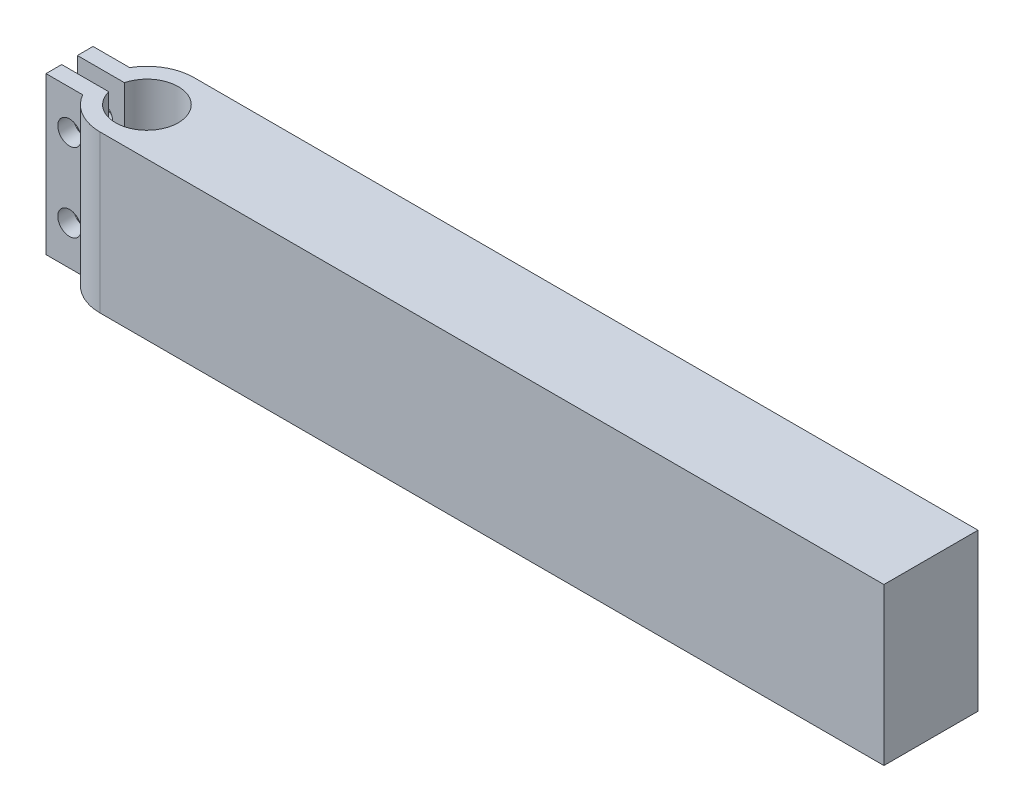
SolidWorks part; units mm, degrees
ref_plane "Plano frontal" through (0, 0, 0) normal (0, 0, 1) x (1, 0, 0)
ref_plane "Plano superior" through (0, 0, 0) normal (0, 1, 0) x (1, 0, 0)
ref_plane "Plano direito" through (0, 0, 0) normal (1, 0, 0) x (0, 0, -1)
sketch "Esboço1" plane through (0, 0, 0) normal (0, 1, 0) x (1, 0, 0)
  line L0 (-2.5769, 7) -> (5.9161, 7) construction
  line L1 (0, 0) -> (100, 0)
  line L2 (0, 0) -> (0, 12)
  line L3 (0, 12) -> (100, 12)
  line L4 (100, 0) -> (100, 12)
  line L9 (0, 0) -> (0, 12)
  circle A0 centre (0, 6) radius 6
  point P9 (52.7164, 7)
  dimension "D1" = 12
  dimension "D2" = 7
  dimension "D3" = 100
extrude "Ressalto-extrusão1" add sketch "Esboço1" along normal blind 20
sketch "Esboço2" plane through (0, 20, 0) normal (0, 1, 0) x (1, 0, 0)
  circle A0 centre (0, 6) radius 4
  dimension "D1" = 8
extrude "Corte-extrusão1" cut sketch "Esboço2" against normal blind 20
sketch "Esboço3" plane through (0, 20, 0) normal (0, 1, 0) x (1, 0, 0)
  line L1 (-9, 7) -> (1, 7)
  line L2 (-9, 7) -> (-9, 5)
  line L3 (-9, 5) -> (1, 5)
  line L4 (1, 7) -> (1, 5)
  line L5 (-9, 7) -> (1, 5) construction
  line L6 (-9, 5) -> (1, 7) construction
  circle A0 centre (0, 6) radius 4 construction
  point P0 (-4, 6)
  dimension "D1" = 10
  dimension "D2" = 2
extrude "Corte-extrusão2" cut sketch "Esboço3" against normal blind 20
sketch "Esboço4" plane through (0, 20, 0) normal (0, 1, 0) x (1, 0, 0)
  line L1 (-3.873, 7) -> (-9.873, 7)
  line L2 (-3.873, 7) -> (-3.873, 9)
  line L3 (-3.873, 9) -> (-9.873, 9)
  line L4 (-9.873, 7) -> (-9.873, 9)
  line L5 (-3.873, 5) -> (-9.873, 5)
  line L6 (-3.873, 5) -> (-3.873, 3)
  line L7 (-3.873, 3) -> (-9.873, 3)
  line L8 (-9.873, 5) -> (-9.873, 3)
  dimension "D1" = 2
  dimension "D2" = 2
  dimension "D3" = 6
  dimension "D4" = 6
extrude "Ressalto-extrusão2" add sketch "Esboço4" against normal blind 20
sketch "Esboço5" plane through (0, 0, -3) normal (0, 0, 1) x (1, 0, 0)
  line L0 (-6.873, 20.1847) -> (-6.873, -3.1303) construction
  line L1 (-9.873, 0) -> (-5.1962, 0) construction
  line L2 (-3.873, 20) -> (-9.873, 20) construction
  line L3 (-9.873, 0) -> (-9.873, 20) construction
  circle A0 centre (-6.873, 15) radius 1.5
  circle A1 centre (-6.873, 5) radius 1.5
  dimension "D1" = 3
  dimension "D2" = 3
  dimension "D3" = 5
  dimension "D4" = 5
  dimension "D5" = 3
extrude "Corte-extrusão3" cut sketch "Esboço5" against normal blind 20
